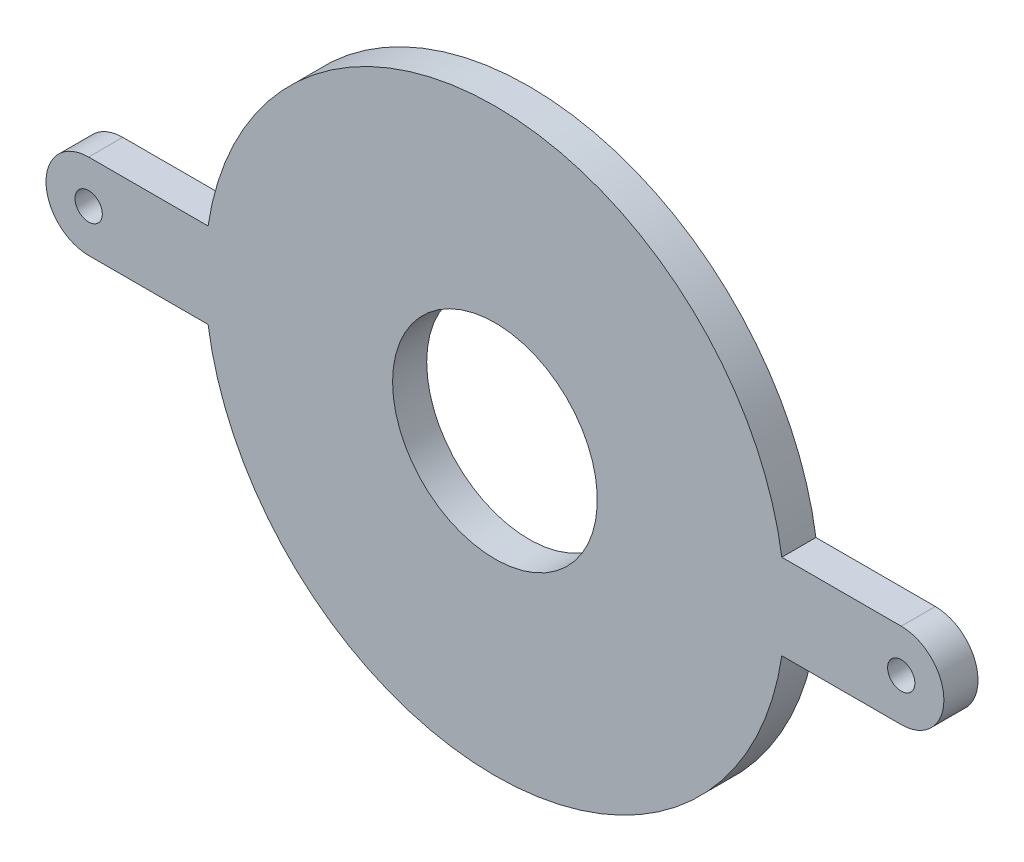
SolidWorks part; units mm, degrees
ref_plane "前视基准面" through (0, 0, 0) normal (0, 0, 1) x (1, 0, 0)
ref_plane "上视基准面" through (0, 0, 0) normal (0, 1, 0) x (1, 0, 0)
ref_plane "右视基准面" through (0, 0, 0) normal (1, 0, 0) x (0, 0, -1)
sketch "草图1" plane through (0, 0, 0) normal (0, 0, 1) x (1, 0, 0)
  circle A1 centre (0, 0) radius 19
  dimension "D1" = 38
extrude "凸台-拉伸1" add sketch "草图1" along normal blind 20
sketch "草图3" plane through (0, 0, 20) normal (0, 0, 1) x (1, 0, 0)
  line L0 (0, 0) -> (0, 10) construction
  line L1 (-22.5, 10) -> (22.5, 10)
  line L3 (22.5, 0) -> (0, 0) construction
  line L4 (-22.5, -10) -> (22.5, -10)
  arc A0 (22.5, -10) -> (22.5, 10) centre (22.5, 0) ccw
  arc A1 (-22.5, 10) -> (-22.5, -10) centre (-22.5, 0) ccw
  point P9 (0, -10)
  dimension "D1" = 22.5
  dimension "D2" = 10
extrude "凸台-拉伸2" add sketch "草图3" against normal blind 3
sketch "草图6" plane through (0, 0, 20) normal (0, 0, 1) x (1, 0, 0)
  circle A0 centre (0, 0) radius 17
  dimension "D1" = 34
extrude "切除-拉伸1" cut sketch "草图6" against normal blind 18
sketch "草图7" plane through (0, 0, 0) normal (0, 0, -1) x (-1, 0, 0)
  circle A0 centre (0, 0) radius 17
  circle A1 centre (0, 0) radius 15
  dimension "D1" = 34
  dimension "D2" = 30
extrude "凸台-拉伸3" add sketch "草图7" along normal blind 9.5
sketch "草图8" plane through (0, 0, 0) normal (0, 0, -1) x (-1, 0, 0)
  circle A0 centre (0, 0) radius 13
  dimension "D1" = 26
extrude "切除-拉伸2" cut sketch "草图8" against normal up to next
sketch "草图10" plane through (0, 0, -9.5) normal (0, 0, -1) x (-1, 0, 0)
  line L0 (-16.8152, 2.5) -> (-23.8152, 2.5)
  line L2 (-23.8152, 0) -> (-17, 0) construction
  line L3 (-16.8152, -2.5) -> (-23.8152, -2.5)
  line L4 (0, 0) -> (0, 16) construction
  line L5 (16.8152, 2.5) -> (23.8152, 2.5)
  line L6 (16.8152, -2.5) -> (23.8152, -2.5)
  circle A0 centre (0, 0) radius 17 construction
  circle A1 centre (0, 0) radius 17 construction
  arc A2 (-16.8152, 2.5) -> (-16.8152, -2.5) centre (0, 0) ccw
  arc A3 (16.8152, -2.5) -> (16.8152, 2.5) centre (0, 0) ccw
  arc A4 (-23.8152, 2.5) -> (-23.8152, -2.5) centre (-23.8152, 0) ccw
  arc A6 (23.8152, 2.5) -> (23.8152, -2.5) centre (23.8152, 0) cw
  dimension "D1" = 7
  dimension "D2" = 2.5
  dimension "D3" = 16
extrude "凸台-拉伸4" add sketch "草图10" against normal blind 2
sketch "草图13" plane through (0, 0, 17) normal (0, 0, -1) x (-1, 0, 0)
  circle A0 centre (-23.8152, 0) radius 5 construction
  point P0 (-23.8152, 0)
  dimension "D1" = 10
hole_wizard "M3 螺纹孔的螺纹孔钻头1" positions "草图13" profile "草图14" hole size "M3" standard "GB"
sketch "草图14" plane through (23.8152, 0, 17) normal (1, 0, 0) x (0, 1, 0)
  line L0 (0, 0) -> (0, 3)
  line L1 (0, 3) -> (1.25, 3)
  line L2 (1.25, 3) -> (1.25, 0)
  line L5 (1.25, 0) -> (0, 0)
  line L11 (0, -6.35) -> (0, 107.95) construction
  dimension "通孔孔直径" = 2.5
  dimension "通孔孔深度" = 3
hole_wizard "M2 螺纹孔的螺纹孔钻头1" positions "草图15" profile "草图16" hole size "M2" standard "GB" end condition up to next
sketch "草图15" plane through (0, 0, -9.5) normal (0, 0, -1) x (-1, 0, 0)
  point P1 (-23.8152, 0)
sketch "草图16" plane through (23.8152, 0, -9.5) normal (1, 0, 0) x (0, 1, 0)
  line L0 (0, 0) -> (0, 2)
  line L1 (0, 2) -> (0.8, 2)
  line L2 (0.8, 2) -> (0.8, 0)
  line L5 (0.8, 0) -> (0, 0)
  line L11 (0, -6.35) -> (0, 107.95) construction
  dimension "通孔孔直径" = 1.6
  dimension "通孔孔深度" = 2
mirror "镜向1" about plane through (0, 0, 0) normal (1, 0, 0) of "M3 螺纹孔的螺纹孔钻头1", "M2 螺纹孔的螺纹孔钻头1"
sketch "草图17" plane through (0, -2.5, 0) normal (0, -1, 0) x (1, 0, 0)
  line L0 (0, 0) -> (0, -7.5) construction
  line L1 (-17, 0) -> (17, 0) construction
  line L2 (-37, -7.5) -> (37, -7.5)
  line L3 (37, -7.5) -> (37, 25.5)
  line L4 (37, 25.5) -> (-37, 25.5)
  line L5 (0, 25.5) -> (0, 0) construction
  line L6 (-37, -7.5) -> (-37, 25.5)
  dimension "D1" = 33
  dimension "D2" = 37
extrude "切除-拉伸3" cut sketch "草图17" against normal through all both and the other way through all
sketch "草图18" plane through (0, 0, -9.5) normal (0, 0, -1) x (-1, 0, 0)
  circle A0 centre (0, 0) radius 15
  circle A1 centre (0, 0) radius 6
  dimension "D1" = 12
extrude "凸台-拉伸5" add sketch "草图18" against normal up to surface (2 mm away) up to face at (23.0152, 0, -7.5)
